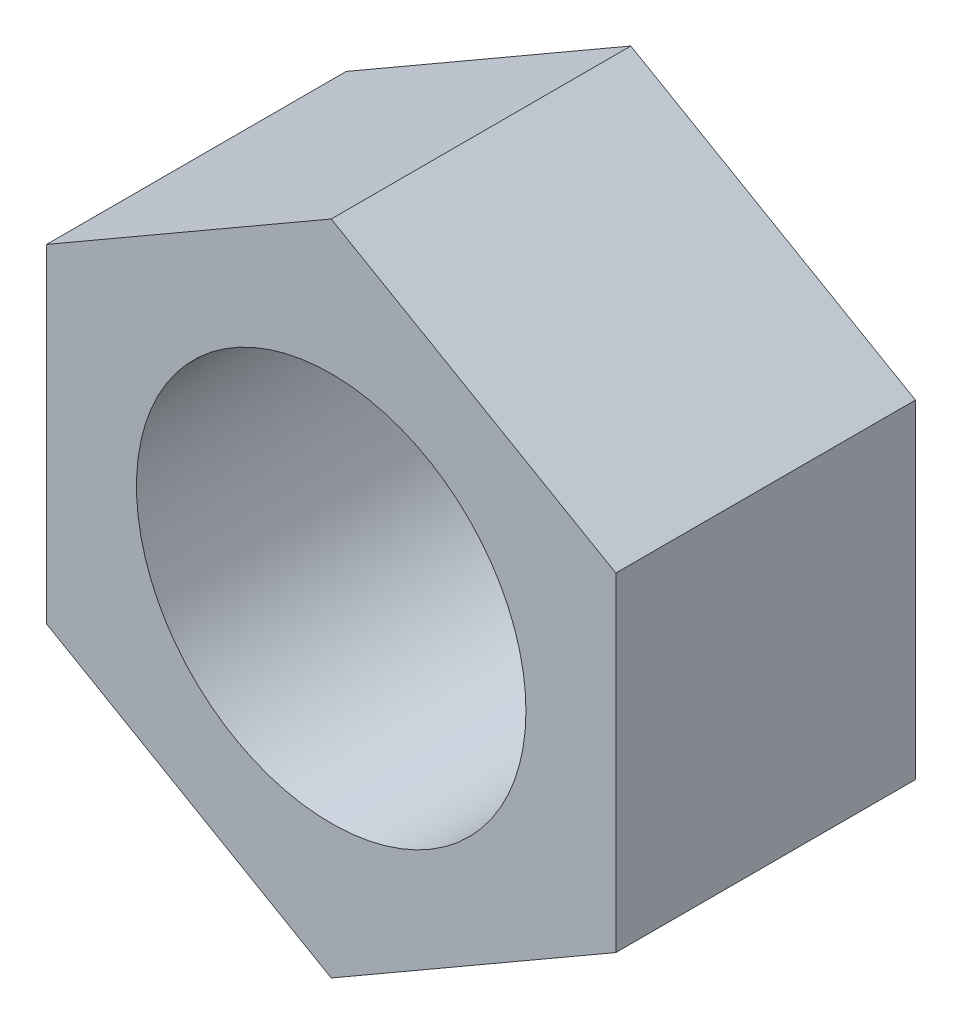
SolidWorks part; units mm, degrees
ref_plane "Front Plane" through (0, 0, 0) normal (0, 0, 1) x (1, 0, 0)
ref_plane "Top Plane" through (0, 0, 0) normal (0, 1, 0) x (1, 0, 0)
ref_plane "Right Plane" through (0, 0, 0) normal (1, 0, 0) x (0, 0, -1)
sketch "Sketch1" plane through (0, 0, 0) normal (0, 0, 1) x (1, 0, 0)
  line L1 (0, 5.4848) -> (-4.75, 2.7424)
  line L2 (-4.75, 2.7424) -> (-4.75, -2.7424)
  line L3 (-4.75, -2.7424) -> (0, -5.4848)
  line L4 (0, -5.4848) -> (4.75, -2.7424)
  line L5 (4.75, -2.7424) -> (4.75, 2.7424)
  line L6 (4.75, 2.7424) -> (0, 5.4848)
  circle A0 centre (0, 0) radius 4.75 construction
  circle A1 centre (0, 0) radius 3.25
  dimension "D2" = 6.5
  dimension "D1" = 9.5
extrude "Boss-Extrude1" add sketch "Sketch1" along normal blind 5
